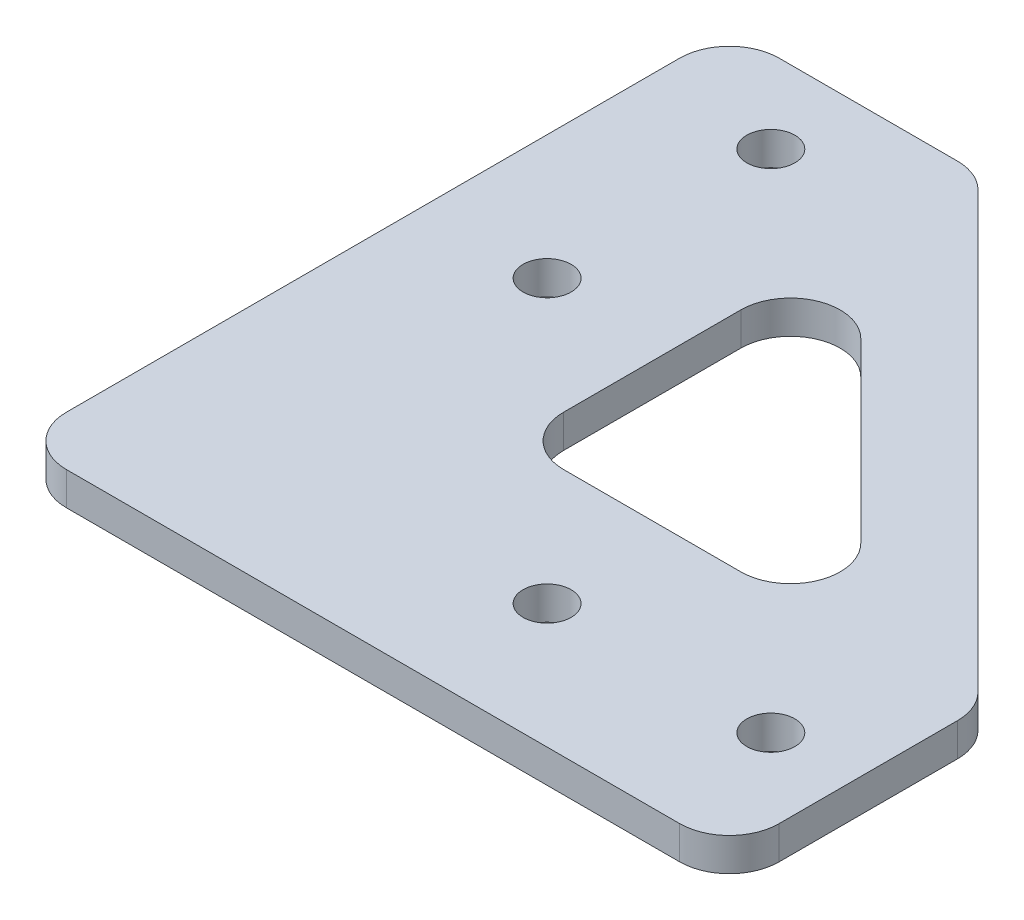
SolidWorks part; units mm, degrees
material "Thornel Mat VMA"
ref_plane "前视基准面" through (0, 0, 0) normal (0, 0, 1) x (1, 0, 0)
ref_plane "上视基准面" through (0, 0, 0) normal (0, 1, 0) x (1, 0, 0)
ref_plane "右视基准面" through (0, 0, 0) normal (1, 0, 0) x (0, 0, -1)
other "Configuration Table"
sketch "草图1" plane through (0, 0, 0) normal (0, 1, 0) x (1, 0, 0)
  line L0 (15, 28) -> (43, 0)
  line L1 (0, 0) -> (15, 0) construction
  line L2 (0, 0) -> (0, 28)
  line L3 (0, 28) -> (15, 28)
  line L4 (15, 0) -> (15, 28) construction
  line L5 (0, 0) -> (43, 0) construction
  line L6 (0, 0) -> (0, -15)
  line L7 (0, -15) -> (43, -15)
  line L8 (43, 0) -> (43, -15)
  line L9 (15, 20.9289) -> (35.9289, 0)
  line L10 (35.9289, 0) -> (15, 0)
  line L11 (15, 0) -> (15, 20.9289)
  line L12 (7.5, -46.7778) -> (7.5, 46.3043) construction
  line L13 (-10.3267, -7.5) -> (76.0569, -7.5) construction
  circle A0 centre (24.5, -7.5) radius 1.45
  circle A1 centre (7.5, 9.5) radius 1.45
  circle A2 centre (38, -7.5) radius 1.45
  circle A3 centre (7.5, 23) radius 1.45
  dimension "D3" = 24.5
  dimension "D6" = 28
  dimension "D7" = 2.9
  dimension "D10" = 5
  dimension "D11" = 5
  dimension "D1" = 15
  dimension "D2" = 5
  dimension "D4" = 24.5
  dimension "D5" = 28
  dimension "D8" = 7.5
  dimension "D9" = 7.5
extrude "凸台-拉伸1" add sketch "草图1" along normal blind 2
fillet "圆角2" radius 3 8 edges at (35.9289, 1, 0) (15, 1, -20.9289) (0, 1, -28) (15, 1, -28) (43, 1, 0) (43, 1, 15) (0, 1, 15) (15, 1, 0)
